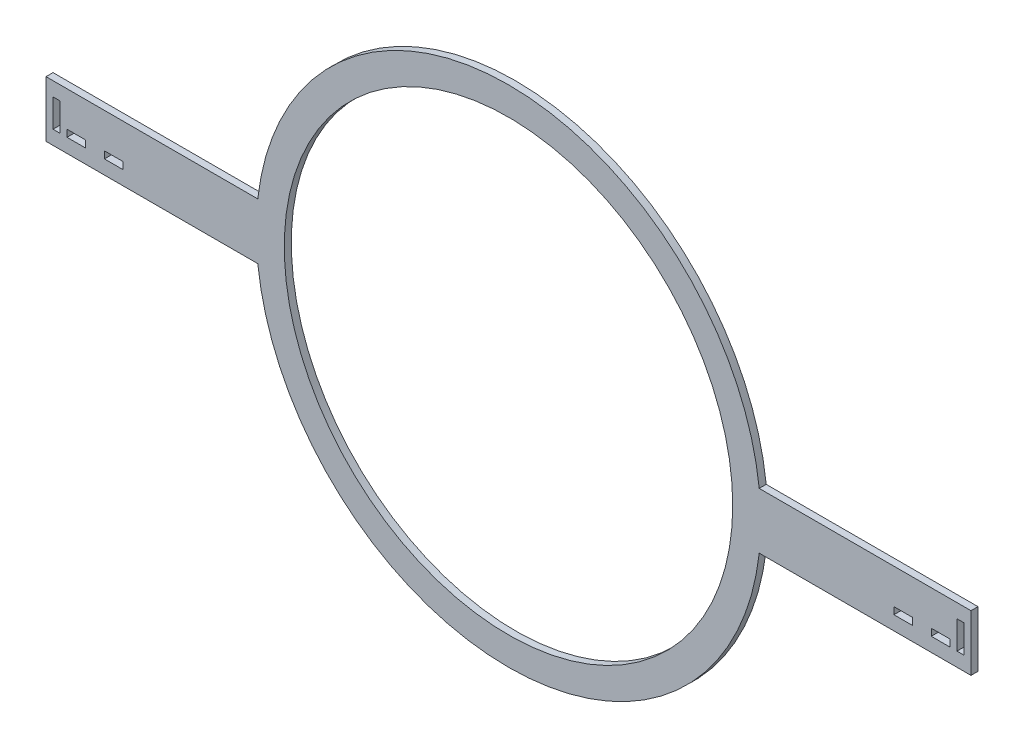
SolidWorks part; units mm, degrees
ref_plane "Front Plane" through (0, 0, 0) normal (0, 0, 1) x (1, 0, 0)
ref_plane "Top Plane" through (0, 0, 0) normal (0, 1, 0) x (1, 0, 0)
ref_plane "Right Plane" through (0, 0, 0) normal (1, 0, 0) x (0, 0, -1)
sketch "Sketch1" plane through (0, 0, 0) normal (0, 0, 1) x (1, 0, 0)
  line L0 (-113.5923, -12.7) -> (-209.55, -12.7)
  line L1 (-209.55, -12.7) -> (-209.55, 12.7)
  line L2 (-209.55, 12.7) -> (-113.5923, 12.7)
  line L3 (0, -55) -> (0, 55) construction
  line L4 (209.55, 12.7) -> (113.5923, 12.7)
  line L5 (113.5923, -12.7) -> (209.55, -12.7)
  line L6 (209.55, -12.7) -> (209.55, 12.7)
  circle A0 centre (0, 0) radius 114.3
  circle A1 centre (0, 0) radius 101.6
  point P6 (-209.55, 0)
  dimension "D1" = 203.2
  dimension "D2" = 12.7
  dimension "D3" = 25.4
  dimension "D4" = 209.55
extrude "Boss-Extrude1" add sketch "Sketch1" along normal blind 3.175 contours A0 L2 L1 L0 | A0 A1 | A0 L5 L6 L4
sketch "Sketch2" plane through (0, 0, 3.175) normal (0, 0, 1) x (1, 0, 0)
  line L0 (-209.55, -12.7) -> (-209.55, 12.7) construction
  line L1 (-206.375, 6.35) -> (-203.2, 6.35)
  line L2 (-206.375, 6.35) -> (-206.375, -6.35)
  line L3 (-206.375, -6.35) -> (-203.2, -6.35)
  line L4 (-203.2, 6.35) -> (-203.2, -6.35)
  point P6 (-206.375, 0)
  dimension "D1" = 3.175
  dimension "D2" = 3.175
  dimension "D3" = 12.7
extrude "Cut-Extrude1" cut sketch "Sketch2" against normal blind 3.175
mirror "Mirror1" about plane through (0, 0, 0) normal (1, 0, 0) of "Cut-Extrude1"
sketch "Sketch3" plane through (0, 0, 3.175) normal (0, 0, 1) x (1, 0, 0)
  line L0 (203.2, -6.35) -> (203.2, 6.35) construction
  line L1 (200.025, -3.175) -> (191.5583, -3.175)
  line L2 (200.025, -3.175) -> (200.025, -6.35)
  line L3 (200.025, -6.35) -> (191.5583, -6.35)
  line L4 (191.5583, -3.175) -> (191.5583, -6.35)
  line L5 (113.5923, -12.7) -> (209.55, -12.7) construction
  line L7 (183.0917, -3.175) -> (174.625, -3.175)
  line L8 (183.0917, -3.175) -> (183.0917, -6.35)
  line L9 (183.0917, -6.35) -> (174.625, -6.35)
  line L10 (174.625, -3.175) -> (174.625, -6.35)
  dimension "D1" = 3.175
  dimension "D2" = 6.35
  dimension "D3" = 8.4667
  dimension "D4" = 3.175
  dimension "D5" = 8.4667
extrude "Cut-Extrude2" cut sketch "Sketch3" against normal blind 3.175
mirror "Mirror2" about plane through (0, 0, 0) normal (1, 0, 0) of "Cut-Extrude2"
